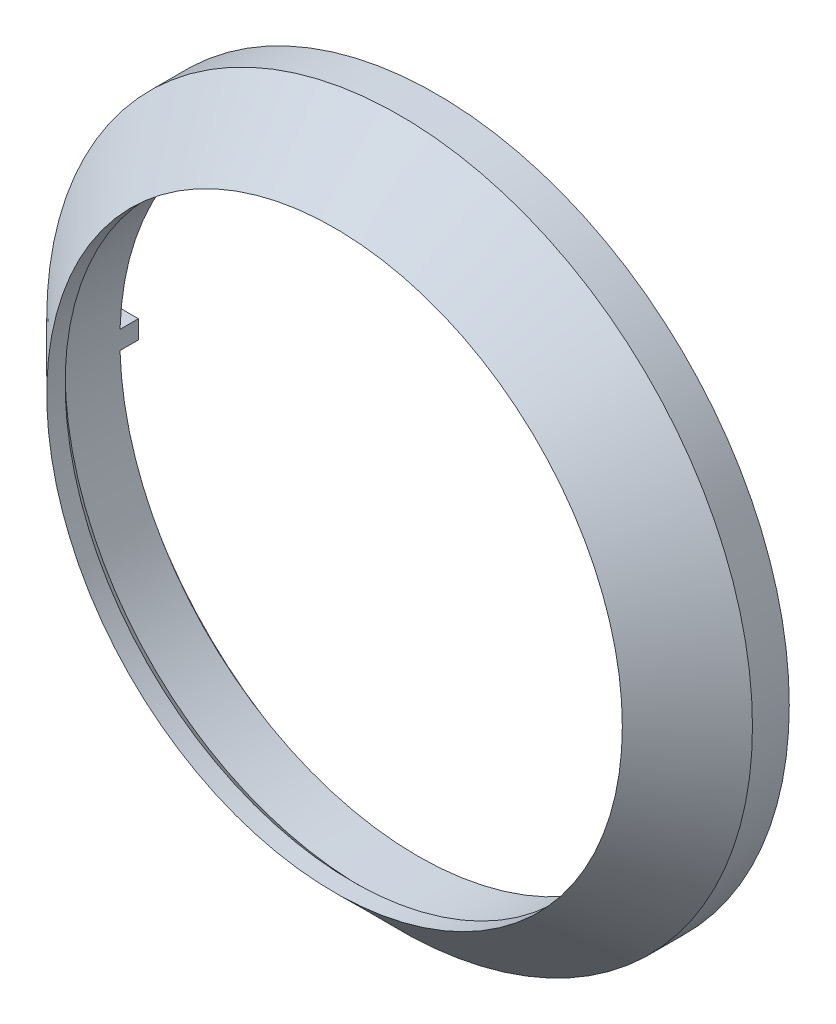
SolidWorks part; units mm, degrees
ref_plane "Plan de face" through (0, 0, 0) normal (0, 0, 1) x (1, 0, 0)
ref_plane "Plan de dessus" through (0, 0, 0) normal (0, 1, 0) x (1, 0, 0)
ref_plane "Plan de droite" through (0, 0, 0) normal (1, 0, 0) x (0, 0, -1)
sketch "Esquisse1" plane through (0, 0, 0) normal (0, 1, 0) x (1, 0, 0)
  line L0 (-81, 0) -> (-87.8697, 0) construction
  line L1 (-87.8697, 0) -> (-87.8697, 5) construction
  line L2 (-87.8697, 5) -> (-95.8697, 5) construction
  line L3 (81, 0) -> (89, 0) construction
  line L4 (89, 0) -> (89, 5) construction
  line L5 (89, 5) -> (95.8697, 5) construction
  line L6 (-95.8697, 5) -> (-95.8697, -5)
  line L7 (-95.8697, -5) -> (-78.192, -22.6777)
  line L8 (-78.192, -22.6777) -> (-78.192, -17.6777)
  line L9 (-78.192, -17.6777) -> (-81, -14.8697)
  line L10 (-81, -14.8697) -> (-81, 0)
  line L11 (-95.8697, 5) -> (-87.8697, 5)
  line L12 (-87.8697, 0) -> (-81, 0)
  line L13 (-87.8697, 0) -> (-87.8697, 5)
  line L14 (0, 0) -> (0, 48.8223) construction
  arc A0 (81, 0) -> (-81, 0) centre (0, 0) ccw construction
  arc A1 (95.8697, 5) -> (-95.8697, 5) centre (0, 0) ccw construction
  dimension "D1" = 96
  dimension "D2" = 8
  dimension "D3" = 15
  dimension "D4" = 8
  dimension "D5" = 5
  dimension "D6" = 5
  dimension "D7" = 10
  dimension "D8" = 135
  dimension "D9" = 5
  dimension "D10" = 25
revolve "Révolution1" add sketch "Esquisse1" angle 360 about L14
sketch "Esquisse6" plane through (0, 0, 0) normal (0, 0, -1) x (-1, 0, 0)
  line L0 (80.9614, -2.5) -> (87.8341, -2.5)
  line L1 (80.9614, 2.5) -> (87.8341, 2.5)
  line L2 (0, 0) -> (13.7584, 0) construction
  arc A1 (80.9614, -2.5) -> (80.9614, 2.5) centre (0, 0) ccw
  circle A5 centre (0, 0) radius 81 construction
  circle A6 centre (0, 0) radius 87.8697 construction
  arc A7 (87.8341, -2.5) -> (87.8341, 2.5) centre (0, 0) ccw
  dimension "D1" = 5
  dimension "D2" = 6.8727
extrude "Boss.-Extru.1" add sketch "Esquisse6" along normal blind 5
mirror "Symétrie1" about plane through (0, 0, 0) normal (1, 0, 0) of "Boss.-Extru.1"
